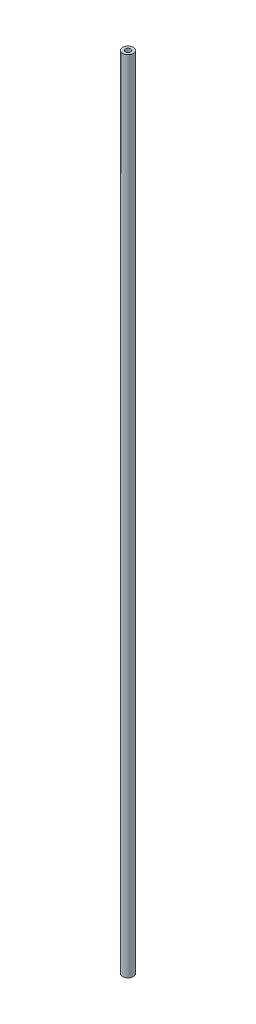
SolidWorks part; units mm, degrees
ref_plane "前视基准面" through (0, 0, 0) normal (0, 0, 1) x (1, 0, 0)
ref_plane "上视基准面" through (0, 0, 0) normal (0, 1, 0) x (1, 0, 0)
ref_plane "右视基准面" through (0, 0, 0) normal (1, 0, 0) x (0, 0, -1)
other "Configuration Table"
sketch "草图1" plane through (0, 0, 0) normal (0, 1, 0) x (1, 0, 0)
  circle A0 centre (0, 0) radius 1
  circle A1 centre (0, 0) radius 0.5
extrude "凸台-拉伸1" add sketch "草图1" along normal blind 150
